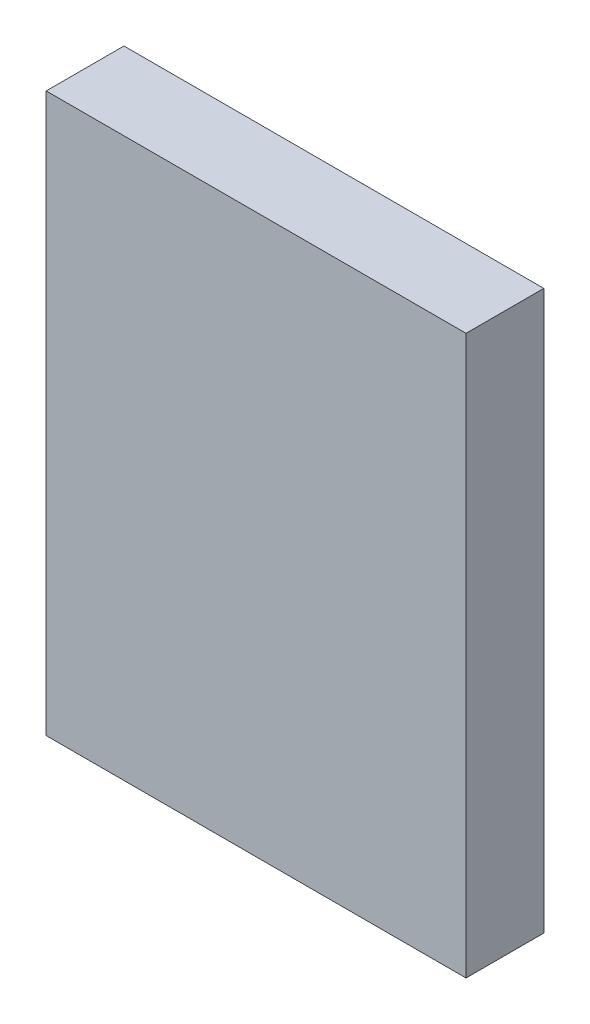
SolidWorks part; units mm, degrees
ref_plane "前视基准面" through (0, 0, 0) normal (0, 0, 1) x (1, 0, 0)
ref_plane "上视基准面" through (0, 0, 0) normal (0, 1, 0) x (1, 0, 0)
ref_plane "右视基准面" through (0, 0, 0) normal (1, 0, 0) x (0, 0, -1)
other "Configuration Table"
sketch "Model" plane through (0, 0, 0) normal (0, 0, 1) x (1, 0, 0)
  line L1 (102.1602, 94.3849) -> (102.1602, 82.3849)
  line L2 (102.1602, 35.8849) -> (102.1602, 29.862)
  line L3 (179.3095, 94.3849) -> (179.3095, 82.3849)
  line L4 (179.3095, 35.8849) -> (179.3095, 29.862)
  line L5 (179.3095, 35.8849) -> (179.3095, 29.862)
  line L6 (139.622, 29.862) -> (102.1602, 29.862)
  line L7 (92.1602, 156.0615) -> (189.3095, 156.0615)
  line L8 (92.1602, 156.0615) -> (92.1602, 26.862)
  line L9 (92.1602, 26.862) -> (189.3095, 26.862)
  line L10 (189.3095, 156.0615) -> (189.3095, 26.862)
  line L11 (102.1856, 29.862) -> (179.3095, 29.862) construction
  line L12 (102.1602, 29.862) -> (179.3095, 29.862) construction
  line L13 (102.1602, 29.862) -> (179.3095, 29.862)
  line L14 (102.1602, 118.9846) -> (102.1602, 126.0615)
  line L16 (179.3095, 29.862) -> (179.3095, 151.036) construction
  line L17 (102.1602, 126.0615) -> (179.3095, 126.0615) construction
  line L18 (179.3095, 126.0615) -> (179.3095, 118.9846)
  line L19 (102.1602, 126.0615) -> (102.1856, 151.036)
  line L20 (102.1856, 151.036) -> (179.3095, 151.036)
  line L21 (179.3095, 151.036) -> (179.3095, 126.0615)
  line L171 (102.1602, 94.3849) -> (102.1602, 118.9846)
  line L172 (102.1602, 35.8849) -> (102.1602, 82.3849)
  line L173 (179.3095, 35.8849) -> (179.3095, 82.3849)
  line L174 (179.3095, 35.8849) -> (179.3095, 82.3849)
  line L175 (179.3095, 118.9846) -> (179.3095, 94.3849)
extrude "凸台-拉伸1" add sketch "Model" along normal blind 15
sketch "草图5" plane through (0, 0, 15) normal (0, 0, 1) x (1, 0, 0)
  line L5 (92.1602, 156.0615) -> (189.3095, 156.0615)
  line L6 (92.1602, 156.0615) -> (92.1602, 26.862)
  line L7 (92.1602, 26.862) -> (189.3095, 26.862)
  line L8 (189.3095, 156.0615) -> (189.3095, 26.862)
extrude "凸台-拉伸2" add sketch "草图5" along normal blind 3
sketch "草图4" plane through (0, 0, 0) normal (0, 0, 1) x (1, 0, 0)
  line L164 (102.1602, 42.3849) -> (102.1602, 17.3849)
  line L186 (179.3095, 100.8849) -> (179.3095, 75.8849)
  line L187 (179.3095, 75.8849) -> (187.3095, 75.8849)
  line L188 (102.1602, 100.8849) -> (102.1602, 75.8849)
  line L189 (102.1602, 100.8849) -> (94.1602, 100.8849)
  line L190 (102.1602, 75.8849) -> (94.1602, 75.8849)
  line L191 (94.1602, 100.8849) -> (94.1602, 75.8849)
  line L192 (187.3095, 100.8849) -> (187.3095, 75.8849)
  line L193 (179.3095, 100.8849) -> (187.3095, 100.8849)
  line L194 (179.3095, 42.3849) -> (179.3095, 17.3849)
  line L195 (179.3095, 42.3849) -> (187.3095, 42.3849)
  line L196 (187.3095, 42.3849) -> (187.3095, 17.3849)
  line L198 (102.1602, 42.3849) -> (94.1602, 42.3849)
  line L199 (102.1602, 17.3849) -> (94.1602, 17.3849)
  line L200 (94.1602, 42.3849) -> (94.1602, 17.3849)
  line L201 (179.3095, 17.3849) -> (187.3095, 17.3849)
extrude "切除-拉伸1" cut sketch "草图4" along normal blind 2
